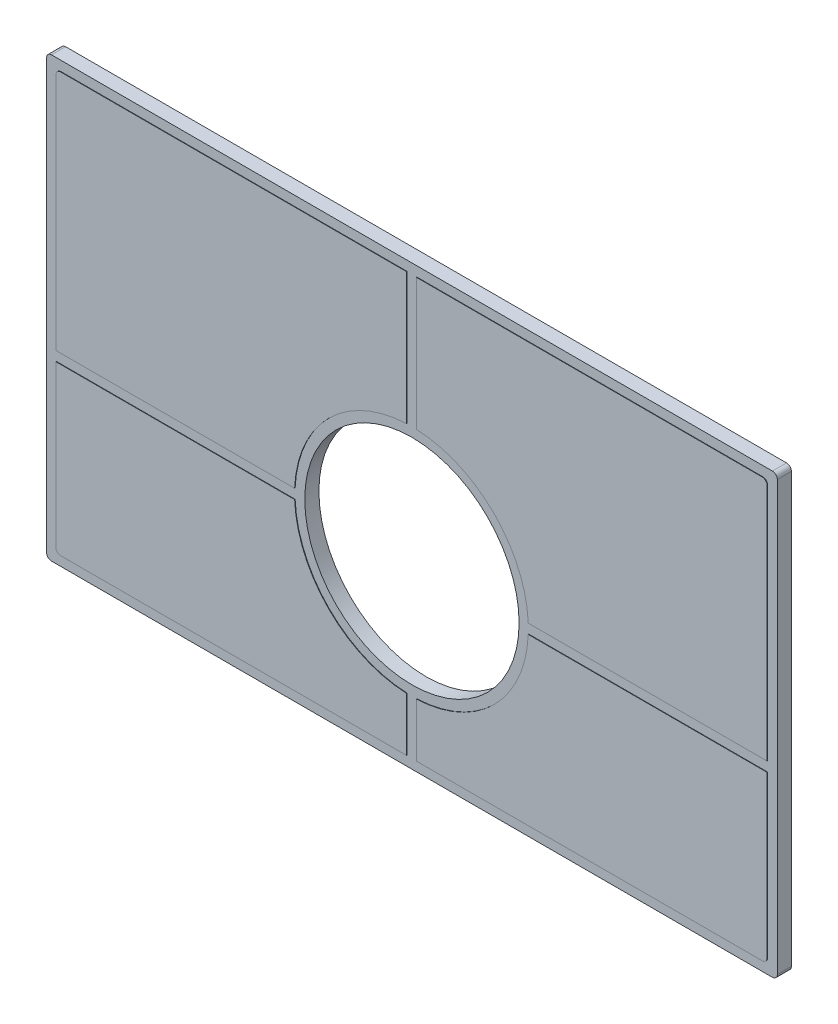
SolidWorks part; units mm, degrees
ref_plane "Спереди" through (0, 0, 0) normal (0, 0, 1) x (1, 0, 0)
ref_plane "Сверху" through (0, 0, 0) normal (0, 1, 0) x (1, 0, 0)
ref_plane "Справа" through (0, 0, 0) normal (1, 0, 0) x (0, 0, -1)
sketch "Эскиз1" plane through (0, 0, 0) normal (0, 0, 1) x (1, 0, 0)
  line L1 (-74, 53) -> (74, 53)
  line L2 (-75, 52) -> (-75, -36)
  line L3 (-74, -37) -> (74, -37)
  line L4 (75, 52) -> (75, -36)
  circle A1 centre (0, 0) radius 22
  arc A2 (74, 53) -> (75, 52) centre (74, 52) cw
  arc A3 (74, -37) -> (75, -36) centre (74, -36) ccw
  arc A4 (-75, -36) -> (-74, -37) centre (-74, -36) ccw
  arc A5 (-74, 53) -> (-75, 52) centre (-74, 52) ccw
  point P9 (75, 53)
  point P12 (75, -37)
  point P17 (-75, 53)
  dimension "D1" = 44
  dimension "D2" = 150
  dimension "D5" = 1
  dimension "D3" = 90
  dimension "D4" = 37
extrude "Бобышка-Вытянуть1" add sketch "Эскиз1" along normal blind 3
sketch "Эскиз6" plane through (0, 0, 3) normal (0, 0, 1) x (1, 0, 0)
  circle A0 centre (0, 0) radius 24
  dimension "48" = 48
extrude "Вырез-Вытянуть1" cut sketch "Эскиз6" against normal blind 0.1
sketch "Эскиз7" plane through (0, 0, 3) normal (0, 0, 1) x (1, 0, 0)
  line L5 (-80.464, 58.3493) -> (81.2544, 58.3493)
  line L6 (-80.464, 58.3493) -> (-80.464, -42.0331)
  line L7 (-80.464, -42.0331) -> (81.2544, -42.0331)
  line L8 (73, 51) -> (-73, 51)
  line L9 (-73, 51) -> (-73, -35)
  line L10 (-73, -35) -> (73, -35)
  line L11 (73, -35) -> (73, 51)
  line L12 (72, 51) -> (-72, 51)
  line L13 (-73, 50) -> (-73, -34)
  line L14 (-72, -35) -> (72, -35)
  line L15 (73, -34) -> (73, 50)
  line L16 (81.2544, 58.3493) -> (81.2544, -42.0331)
  arc A4 (72, 51) -> (73, 50) centre (72, 50) cw
  arc A5 (72, -35) -> (73, -34) centre (72, -34) ccw
  arc A6 (-73, -34) -> (-72, -35) centre (-72, -34) ccw
  arc A7 (-72, 51) -> (-73, 50) centre (-72, 50) ccw
  dimension "D2" = 1
  dimension "D1" = 2
extrude "Вырез-Вытянуть2" cut sketch "Эскиз7" against normal blind 0.1
sketch "Эскиз8" plane through (0, 0, 3) normal (0, 0, 1) x (1, 0, 0)
  line L1 (-1, 55.9781) -> (1, 55.9781)
  line L2 (-1, 55.9781) -> (-1, -45.669)
  line L3 (-1, -45.669) -> (1, -45.669)
  line L4 (1, 55.9781) -> (1, -45.669)
  point P4 (0, 55.9781)
  point P6 (1, 55.9781)
  dimension "D1" = 0
  dimension "D2" = 2
extrude "Вырез-Вытянуть3" cut sketch "Эскиз8" against normal blind 0.1
sketch "Эскиз9" plane through (0, 0, 3) normal (0, 0, 1) x (1, 0, 0)
  line L1 (-85.9969, 1) -> (99.4339, 1)
  line L2 (-85.9969, 1) -> (-85.9969, -1)
  line L3 (-85.9969, -1) -> (99.4339, -1)
  line L4 (99.4339, 1) -> (99.4339, -1)
  point P4 (99.4339, 0)
  dimension "D1" = 0
  dimension "D2" = 2
extrude "Вырез-Вытянуть4" cut sketch "Эскиз9" against normal blind 0.1
